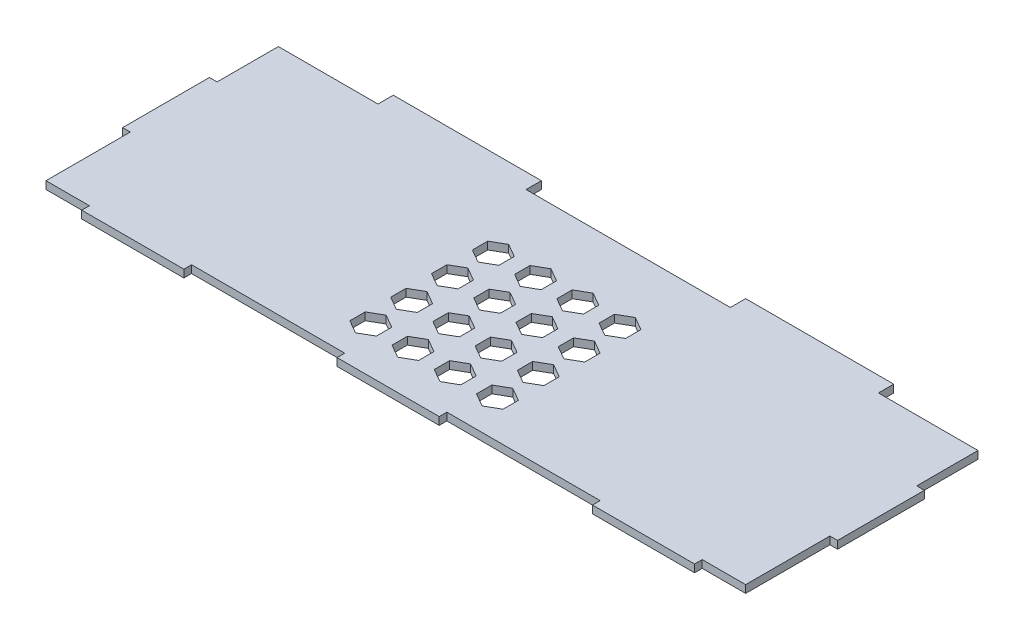
SolidWorks part; units mm, degrees
ref_plane "Front Plane" through (0, 0, 0) normal (0, 0, 1) x (1, 0, 0)
ref_plane "Top Plane" through (0, 0, 0) normal (0, 1, 0) x (1, 0, 0)
ref_plane "Right Plane" through (0, 0, 0) normal (1, 0, 0) x (0, 0, -1)
sketch "Sketch2" plane through (0, 0, 0) normal (0, 1, 0) x (1, 0, 0)
  line L5 (-70, 23.5) -> (-49, 23.5)
  line L6 (70, -23.5) -> (-70, -23.5)
  line L15 (70, -23.5) -> (70, 23.5)
  line L17 (-70, -23.5) -> (-70, 23.5)
  line L18 (70, -23.5) -> (-70, 23.5) construction
  line L19 (70, 23.5) -> (-70, -23.5) construction
  line L20 (-49, 23.5) -> (-49, 26.5)
  line L21 (-49, 26.5) -> (-20, 26.5)
  line L22 (-20, 26.5) -> (-20, 23.5)
  line L24 (20, 23.5) -> (20, 26.5)
  line L25 (20, 26.5) -> (49, 26.5)
  line L26 (49, 26.5) -> (49, 23.5)
  line L27 (49, 23.5) -> (70, 23.5)
  line L28 (-20, 23.5) -> (20, 23.5)
  point P0 (0, 0)
  dimension "D1" = 140
  dimension "D2" = 47
  dimension "D3" = 140
  dimension "D4" = 21
  dimension "D5" = 29
  dimension "D6" = 29
  dimension "D7" = 21
  dimension "D8" = 40
  dimension "D9" = 3
  dimension "D10" = 3
  dimension "D11" = 47
extrude "Boss-Extrude1" add sketch "Sketch2" along normal blind 1.5
sketch "Sketch5" plane through (0, 1.5, 0) normal (0, 1, 0) x (1, 0, 0)
  line L0 (-4.134, -11.5) -> (-6.7321, -13)
  line L1 (-12.4019, -11.5) -> (-15, -13)
  line L2 (-15, -13) -> (-15, -16)
  line L3 (-15, -16) -> (-12.4019, -17.5)
  line L4 (-12.4019, -17.5) -> (-9.8038, -16)
  line L5 (-9.8038, -16) -> (-9.8038, -13)
  line L6 (-9.8038, -13) -> (-12.4019, -11.5)
  line L7 (-6.7321, -13) -> (-6.7321, -16)
  line L8 (-6.7321, -16) -> (-4.134, -17.5)
  line L9 (-4.134, -17.5) -> (-1.5359, -16)
  line L10 (-1.5359, -16) -> (-1.5359, -13)
  line L11 (-1.5359, -13) -> (-4.134, -11.5)
  line L12 (4.134, -11.5) -> (1.5359, -13)
  line L13 (1.5359, -13) -> (1.5359, -16)
  line L14 (1.5359, -16) -> (4.134, -17.5)
  line L15 (4.134, -17.5) -> (6.7321, -16)
  line L16 (6.7321, -16) -> (6.7321, -13)
  line L17 (6.7321, -13) -> (4.134, -11.5)
  line L18 (12.4019, -11.5) -> (9.8038, -13)
  line L19 (9.8038, -13) -> (9.8038, -16)
  line L20 (9.8038, -16) -> (12.4019, -17.5)
  line L21 (12.4019, -17.5) -> (15, -16)
  line L22 (15, -16) -> (15, -13)
  line L23 (15, -13) -> (12.4019, -11.5)
  line L24 (-4.134, -3.5) -> (-6.7321, -5)
  line L25 (-6.7321, -5) -> (-6.7321, -8)
  line L26 (-6.7321, -8) -> (-4.134, -9.5)
  line L27 (-4.134, -9.5) -> (-1.5359, -8)
  line L28 (-1.5359, -8) -> (-1.5359, -5)
  line L29 (-1.5359, -5) -> (-4.134, -3.5)
  line L30 (4.134, -3.5) -> (1.5359, -5)
  line L31 (1.5359, -5) -> (1.5359, -8)
  line L32 (1.5359, -8) -> (4.134, -9.5)
  line L33 (4.134, -9.5) -> (6.7321, -8)
  line L34 (6.7321, -8) -> (6.7321, -5)
  line L35 (6.7321, -5) -> (4.134, -3.5)
  line L36 (12.4019, -3.5) -> (9.8038, -5)
  line L37 (9.8038, -5) -> (9.8038, -8)
  line L38 (9.8038, -8) -> (12.4019, -9.5)
  line L39 (12.4019, -9.5) -> (15, -8)
  line L40 (15, -8) -> (15, -5)
  line L41 (15, -5) -> (12.4019, -3.5)
  line L42 (-4.134, 4.5) -> (-6.7321, 3)
  line L43 (-6.7321, 3) -> (-6.7321, 0)
  line L44 (-6.7321, 0) -> (-4.134, -1.5)
  line L45 (-4.134, -1.5) -> (-1.5359, 0)
  line L46 (-1.5359, 0) -> (-1.5359, 3)
  line L47 (-1.5359, 3) -> (-4.134, 4.5)
  line L48 (4.134, 4.5) -> (1.5359, 3)
  line L49 (1.5359, 3) -> (1.5359, 0)
  line L50 (1.5359, 0) -> (4.134, -1.5)
  line L51 (4.134, -1.5) -> (6.7321, 0)
  line L52 (6.7321, 0) -> (6.7321, 3)
  line L53 (6.7321, 3) -> (4.134, 4.5)
  line L54 (12.4019, 4.5) -> (9.8038, 3)
  line L55 (9.8038, 3) -> (9.8038, 0)
  line L56 (9.8038, 0) -> (12.4019, -1.5)
  line L57 (12.4019, -1.5) -> (15, 0)
  line L58 (15, 0) -> (15, 3)
  line L59 (15, 3) -> (12.4019, 4.5)
  line L60 (-4.134, 12.5) -> (-6.7321, 11)
  line L61 (-6.7321, 11) -> (-6.7321, 8)
  line L62 (-6.7321, 8) -> (-4.134, 6.5)
  line L63 (-4.134, 6.5) -> (-1.5359, 8)
  line L64 (-1.5359, 8) -> (-1.5359, 11)
  line L65 (-1.5359, 11) -> (-4.134, 12.5)
  line L66 (4.134, 12.5) -> (1.5359, 11)
  line L67 (1.5359, 11) -> (1.5359, 8)
  line L68 (1.5359, 8) -> (4.134, 6.5)
  line L69 (4.134, 6.5) -> (6.7321, 8)
  line L70 (6.7321, 8) -> (6.7321, 11)
  line L71 (6.7321, 11) -> (4.134, 12.5)
  line L72 (12.4019, 12.5) -> (9.8038, 11)
  line L73 (9.8038, 11) -> (9.8038, 8)
  line L74 (9.8038, 8) -> (12.4019, 6.5)
  line L75 (12.4019, 6.5) -> (15, 8)
  line L76 (15, 8) -> (15, 11)
  line L77 (15, 11) -> (12.4019, 12.5)
  line L78 (-12.4019, -3.5) -> (-15, -5)
  line L79 (-15, -5) -> (-15, -8)
  line L80 (-15, -8) -> (-12.4019, -9.5)
  line L81 (-12.4019, -9.5) -> (-9.8038, -8)
  line L82 (-9.8038, -8) -> (-9.8038, -5)
  line L83 (-9.8038, -5) -> (-12.4019, -3.5)
  line L84 (-12.4019, 4.5) -> (-15, 3)
  line L85 (-15, 3) -> (-15, 0)
  line L86 (-15, 0) -> (-12.4019, -1.5)
  line L87 (-12.4019, -1.5) -> (-9.8038, 0)
  line L88 (-9.8038, 0) -> (-9.8038, 3)
  line L89 (-9.8038, 3) -> (-12.4019, 4.5)
  line L90 (-12.4019, 12.5) -> (-15, 11)
  line L91 (-15, 11) -> (-15, 8)
  line L92 (-15, 8) -> (-12.4019, 6.5)
  line L93 (-12.4019, 6.5) -> (-9.8038, 8)
  line L94 (-9.8038, 8) -> (-9.8038, 11)
  line L95 (-9.8038, 11) -> (-12.4019, 12.5)
  line L99 (20, 23.5) -> (-20, 23.5) construction
  line L100 (-70, 23.5) -> (-70, -23.5) construction
  line L101 (70, -23.5) -> (70, 23.5) construction
  circle A0 centre (-12.4019, -14.5) radius 2.5981 construction
  dimension "D1" = 3
  dimension "D4" = 55
  dimension "D5" = 55
  dimension "D6" = 14.5
  dimension "D7" = 8
  dimension "D8" = 11
  dimension "D2" = 4
  dimension "D3" = 4
extrude "Cut-Extrude1" cut sketch "Sketch5" against normal through all
sketch "Sketch6" plane through (0, 1.5, 0) normal (0, 1, 0) x (1, 0, 0)
  line L0 (70, 23.5) -> (68.5, 23.5)
  line L1 (70, 23.5) -> (49, 23.5) construction
  line L2 (68.5, 23.5) -> (68.5, 11.5)
  line L4 (70, -23.5) -> (70, 23.5) construction
  line L9 (70, 11.5) -> (70, 23.5)
  line L10 (68.5, -5.5) -> (68.5, -23.5)
  line L11 (-70, -23.5) -> (70, -23.5) construction
  line L12 (68.5, -23.5) -> (70, -23.5)
  line L13 (70, -23.5) -> (70, -5.5)
  line L14 (70, -23.5) -> (70, -22)
  line L15 (70, -22) -> (60, -22)
  line L16 (60, -22) -> (60, -23.5)
  line L17 (60, -23.5) -> (70, -23.5)
  line L18 (40, -23.5) -> (40, -22)
  line L19 (40, -22) -> (10, -22)
  line L20 (10, -22) -> (10, -23.5)
  line L21 (10, -23.5) -> (40, -23.5)
  line L22 (-10, -23.5) -> (-10, -22)
  line L23 (-10, -22) -> (-40, -22)
  line L24 (-40, -22) -> (-40, -23.5)
  line L25 (-40, -23.5) -> (-10, -23.5)
  line L26 (-70, 23.5) -> (-68.5, 23.5)
  line L27 (-49, 23.5) -> (-70, 23.5) construction
  line L28 (-68.5, 23.5) -> (-68.5, 11.5)
  line L29 (-68.5, 11.5) -> (-70, 11.5)
  line L30 (-70, 23.5) -> (-70, -23.5) construction
  line L31 (-70, 11.5) -> (-70, 23.5)
  line L32 (-70, -5.5) -> (-68.5, -5.5)
  line L33 (-68.5, -5.5) -> (-68.5, -23.5)
  line L34 (-68.5, -23.5) -> (-70, -23.5)
  line L35 (-70, -23.5) -> (-70, -5.5)
  line L36 (-70, -23.5) -> (-60, -23.5)
  line L37 (-60, -23.5) -> (-60, -22)
  line L38 (-60, -22) -> (-70, -22)
  line L39 (-70, -22) -> (-70, -23.5)
  line L40 (68.5, -5.5) -> (70, -5.5)
  line L41 (70, 11.5) -> (68.5, 11.5)
  dimension "D1" = 1.5
  dimension "D2" = 12
  dimension "D3" = 1.5
  dimension "D4" = 18
  dimension "D5" = 10
  dimension "D6" = 1.5
  dimension "D7" = 1.5
  dimension "D8" = 12
  dimension "D9" = 1.5
  dimension "D10" = 18
  dimension "D11" = 10
  dimension "D12" = 1.5
  dimension "D13" = 30
  dimension "D14" = 30
  dimension "D15" = 20
  dimension "D16" = 20
  dimension "D17" = 1.5
  dimension "D18" = 1.5
extrude "Cut-Extrude2" cut sketch "Sketch6" against normal through all contours L41 L9 L0 L2 | L20 L21 L18 L19 | L16 L17 L10 L15 | L37 L38 L33 L36 | L38 L33 L32 L35 | L33 L38 L35 L34 | L31 L26 L28 L29 | L23 L24 L25 L22
